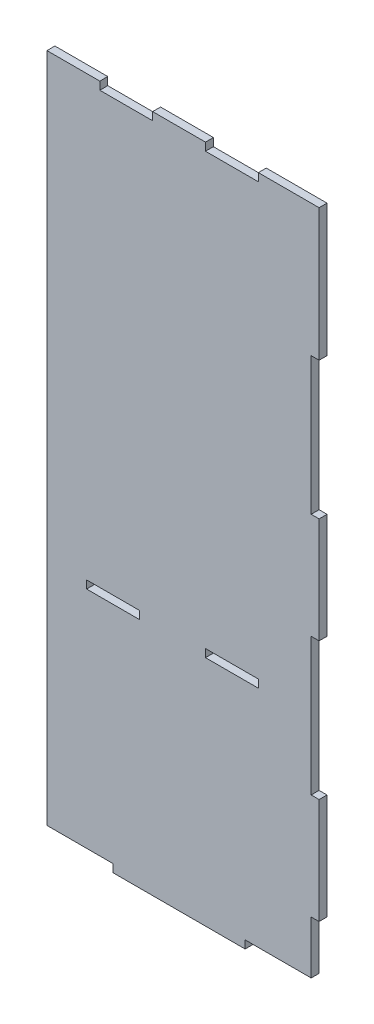
SolidWorks part; units mm, degrees
ref_plane "Front Plane" through (0, 0, 0) normal (0, 0, 1) x (1, 0, 0)
ref_plane "Top Plane" through (0, 0, 0) normal (0, 1, 0) x (1, 0, 0)
ref_plane "Right Plane" through (0, 0, 0) normal (1, 0, 0) x (0, 0, -1)
sketch "Sketch1" plane through (0, 0, 0) normal (0, 0, 1) x (1, 0, 0)
  line L1 (-59.2521, 98.681) -> (40.7479, 98.681)
  line L2 (-59.2521, 98.681) -> (-59.2521, -155.319)
  line L3 (-59.2521, -155.319) -> (40.7479, -155.319)
  line L4 (40.7479, 98.681) -> (40.7479, -155.319)
  dimension "D1" = 254
  dimension "D2" = 100
extrude "Boss-Extrude1" add sketch "Sketch1" along normal blind 3
sketch "Sketch2" plane through (0, -155.319, 0) normal (0, -1, 0) x (1, 0, 0)
  line L0 (-59.2521, 3) -> (40.7479, 3) construction
  line L1 (-34.2521, 3) -> (15.7479, 3)
  line L2 (-34.2521, 3) -> (-34.2521, 0)
  line L3 (-34.2521, 0) -> (15.7479, 0)
  line L4 (15.7479, 3) -> (15.7479, 0)
  line L5 (-59.2521, 0) -> (40.7479, 0) construction
  line L6 (40.7479, 3) -> (40.7479, 0) construction
  dimension "D1" = 50
  dimension "D2" = 25
extrude "Boss-Extrude2" add sketch "Sketch2" along normal blind 3
sketch "Sketch3" plane through (0, 98.681, 0) normal (0, 1, 0) x (1, 0, 0)
  line L0 (40.7479, 0) -> (-59.2521, 0) construction
  line L1 (-19.2521, 0) -> (-39.2521, 0)
  line L2 (-19.2521, 0) -> (-19.2521, -3)
  line L3 (-19.2521, -3) -> (-39.2521, -3)
  line L4 (-39.2521, 0) -> (-39.2521, -3)
  line L5 (40.7479, -3) -> (-59.2521, -3) construction
  line L6 (-59.2521, -3) -> (-59.2521, 0) construction
  line L7 (43.7479, 0) -> (43.7479, -3) construction
  line L8 (0.7479, 0) -> (20.7479, 0)
  line L9 (0.7479, 0) -> (0.7479, -3)
  line L10 (0.7479, -3) -> (20.7479, -3)
  line L11 (20.7479, 0) -> (20.7479, -3)
  dimension "D1" = 20
  dimension "D2" = 20
  dimension "D3" = 20
  dimension "D4" = 23
extrude "Cut-Extrude1" cut sketch "Sketch3" against normal blind 3
sketch "Sketch4" plane through (40.7479, 0, 0) normal (1, 0, 0) x (0, 0, -1)
  line L0 (0, -155.319) -> (0, 98.681) construction
  line L1 (0, -135.319) -> (-3, -135.319)
  line L2 (0, -135.319) -> (0, -95.319)
  line L3 (0, -95.319) -> (-3, -95.319)
  line L4 (-3, -135.319) -> (-3, -95.319)
  line L5 (-3, -155.319) -> (-3, 98.681) construction
  line L6 (40, -155.319) -> (-10, -155.319) construction
  line L8 (-3, -43.319) -> (0, -43.319)
  line L9 (-3, -43.319) -> (-3, -3.319)
  line L10 (-3, -3.319) -> (0, -3.319)
  line L11 (0, -43.319) -> (0, -3.319)
  line L12 (0, 98.681) -> (-3, 98.681)
  line L13 (0, 98.681) -> (0, 48.681)
  line L14 (0, 48.681) -> (-3, 48.681)
  line L15 (-3, 98.681) -> (-3, 48.681)
  dimension "D1" = 40
  dimension "D2" = 20
  dimension "D3" = 40
  dimension "D4" = 52
  dimension "D5" = 50
extrude "Boss-Extrude3" add sketch "Sketch4" along normal blind 3 contours L13 L14 L15 L12 | L9 L10 L11 L8 | L4 L3 L2 L1
sketch "Sketch5" plane through (0, 0, 0) normal (0, 0, -1) x (-1, 0, 0)
  line L1 (-20.7479, -67.319) -> (-0.7479, -67.319)
  line L2 (-20.7479, -67.319) -> (-20.7479, -70.319)
  line L3 (-20.7479, -70.319) -> (-0.7479, -70.319)
  line L4 (-0.7479, -67.319) -> (-0.7479, -70.319)
  line L5 (24.2521, -67.319) -> (44.2521, -67.319)
  line L6 (24.2521, -67.319) -> (24.2521, -70.319)
  line L7 (24.2521, -70.319) -> (44.2521, -70.319)
  line L8 (44.2521, -67.319) -> (44.2521, -70.319)
extrude "Cut-Extrude2" cut sketch "Sketch5" against normal blind 3
